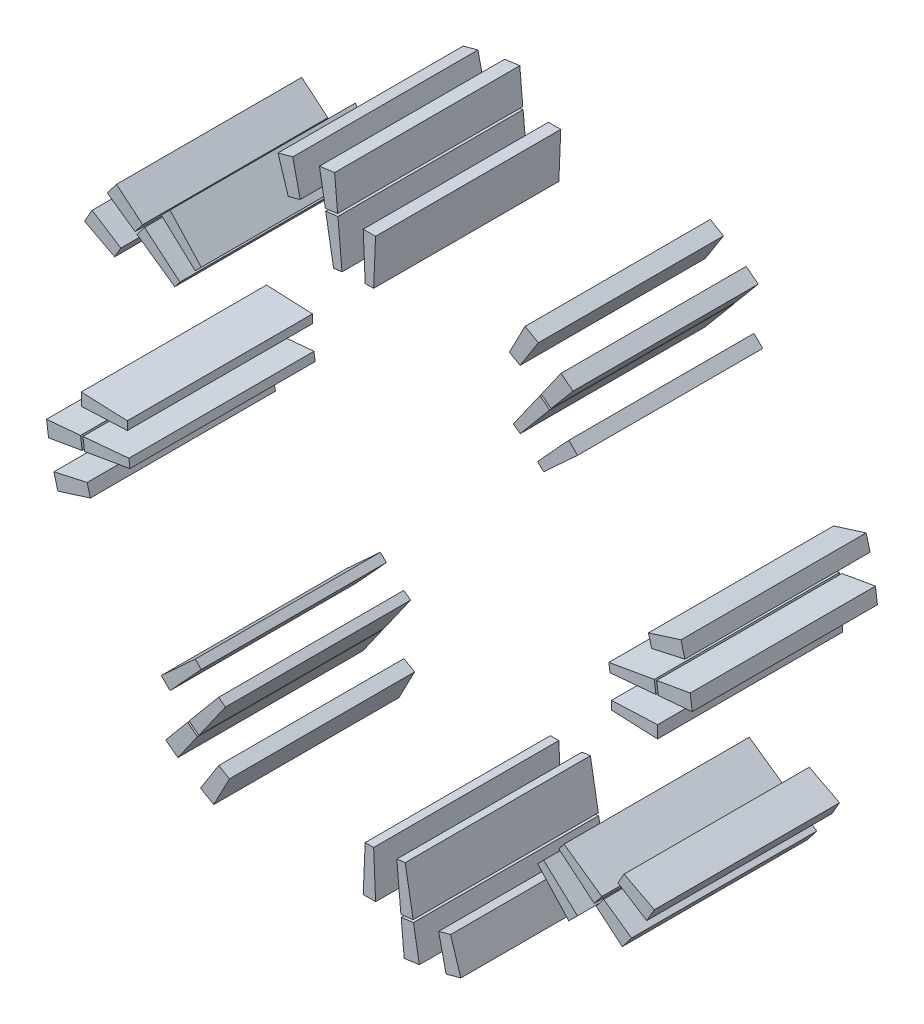
SolidWorks part; units mm, degrees
ref_plane "Спереди" through (0, 0, 0) normal (0, 0, 1) x (1, 0, 0)
ref_plane "Сверху" through (0, 0, 0) normal (0, 1, 0) x (1, 0, 0)
ref_plane "Справа" through (0, 0, 0) normal (1, 0, 0) x (0, 0, -1)
sketch "Эскиз1" plane through (0, 0, 0) normal (0, 0, 1) x (1, 0, 0)
  line L0 (39.2171, -0.6875) -> (46.6769, -1.0008)
  line L1 (46.6769, -1.0008) -> (46.6769, 1.0008)
  line L2 (46.6769, 1.0008) -> (39.2171, 0.6875)
  line L3 (39.2171, 0.6875) -> (39.2171, -0.6875)
  line L4 (46.7943, 5.1511) -> (52.2963, 5.6368)
  line L5 (52.2963, 5.6368) -> (51.9732, 8.0906)
  line L6 (51.9732, 8.0906) -> (46.533, 7.1357)
  line L7 (46.533, 7.1357) -> (46.7943, 5.1511)
  line L8 (38.9713, 4.4372) -> (46.4082, 5.1003)
  line L9 (46.4082, 5.1003) -> (46.147, 7.0848)
  line L10 (46.147, 7.0848) -> (38.7918, 5.8005)
  line L11 (38.7918, 5.8005) -> (38.9713, 4.4372)
  line L12 (45.7216, 11.2149) -> (51.1131, 12.4146)
  line L13 (51.1131, 12.4146) -> (50.4725, 14.8052)
  line L14 (50.4725, 14.8052) -> (45.2035, 13.1484)
  line L15 (45.2035, 13.1484) -> (45.7216, 11.2149)
  line L16 (28.2168, 27.2445) -> (33.7133, 32.2979)
  line L17 (33.7133, 32.2979) -> (32.2979, 33.7133)
  line L18 (32.2979, 33.7133) -> (27.2445, 28.2168)
  line L19 (27.2445, 28.2168) -> (28.2168, 27.2445)
  line L20 (29.4462, 36.7309) -> (32.9933, 40.9648)
  line L21 (32.9933, 40.9648) -> (31.0297, 42.4715)
  line L22 (31.0297, 42.4715) -> (27.8581, 37.9495)
  line L23 (27.8581, 37.9495) -> (29.4462, 36.7309)
  line L24 (24.4193, 30.6945) -> (29.2091, 36.422)
  line L25 (29.2091, 36.422) -> (27.6211, 37.6406)
  line L26 (27.6211, 37.6406) -> (23.3284, 31.5315)
  line L27 (23.3284, 31.5315) -> (24.4193, 30.6945)
  line L28 (24.3999, 40.2602) -> (27.364, 44.9209)
  line L29 (27.364, 44.9209) -> (25.2206, 46.1584)
  line L30 (25.2206, 46.1584) -> (22.6664, 41.261)
  line L31 (22.6664, 41.261) -> (24.3999, 40.2602)
  line L32 (0.6875, 39.2171) -> (1.0008, 46.6769)
  line L33 (1.0008, 46.6769) -> (-1.0008, 46.6769)
  line L34 (-1.0008, 46.6769) -> (-0.6875, 39.2171)
  line L35 (-0.6875, 39.2171) -> (0.6875, 39.2171)
  line L36 (-5.1511, 46.7943) -> (-5.6368, 52.2963)
  line L37 (-5.6368, 52.2963) -> (-8.0906, 51.9732)
  line L38 (-8.0906, 51.9732) -> (-7.1357, 46.533)
  line L39 (-7.1357, 46.533) -> (-5.1511, 46.7943)
  line L40 (-4.4372, 38.9713) -> (-5.1003, 46.4082)
  line L41 (-5.1003, 46.4082) -> (-7.0848, 46.147)
  line L42 (-7.0848, 46.147) -> (-5.8005, 38.7918)
  line L43 (-5.8005, 38.7918) -> (-4.4372, 38.9713)
  line L44 (-11.2149, 45.7216) -> (-12.4146, 51.1131)
  line L45 (-12.4146, 51.1131) -> (-14.8052, 50.4725)
  line L46 (-14.8052, 50.4725) -> (-13.1484, 45.2035)
  line L47 (-13.1484, 45.2035) -> (-11.2149, 45.7216)
  line L48 (-27.2445, 28.2168) -> (-32.2979, 33.7133)
  line L49 (-32.2979, 33.7133) -> (-33.7133, 32.2979)
  line L50 (-33.7133, 32.2979) -> (-28.2168, 27.2445)
  line L51 (-28.2168, 27.2445) -> (-27.2445, 28.2168)
  line L52 (-36.7309, 29.4462) -> (-40.9648, 32.9933)
  line L53 (-40.9648, 32.9933) -> (-42.4715, 31.0297)
  line L54 (-42.4715, 31.0297) -> (-37.9495, 27.8581)
  line L55 (-37.9495, 27.8581) -> (-36.7309, 29.4462)
  line L56 (-30.6945, 24.4193) -> (-36.422, 29.2091)
  line L57 (-36.422, 29.2091) -> (-37.6406, 27.6211)
  line L58 (-37.6406, 27.6211) -> (-31.5315, 23.3284)
  line L59 (-31.5315, 23.3284) -> (-30.6945, 24.4193)
  line L60 (-40.2602, 24.3999) -> (-44.9209, 27.364)
  line L61 (-44.9209, 27.364) -> (-46.1584, 25.2206)
  line L62 (-46.1584, 25.2206) -> (-41.261, 22.6664)
  line L63 (-41.261, 22.6664) -> (-40.2602, 24.3999)
  line L64 (-39.2171, 0.6875) -> (-46.6769, 1.0008)
  line L65 (-46.6769, 1.0008) -> (-46.6769, -1.0008)
  line L66 (-46.6769, -1.0008) -> (-39.2171, -0.6875)
  line L67 (-39.2171, -0.6875) -> (-39.2171, 0.6875)
  line L68 (-46.7943, -5.1511) -> (-52.2963, -5.6368)
  line L69 (-52.2963, -5.6368) -> (-51.9732, -8.0906)
  line L70 (-51.9732, -8.0906) -> (-46.533, -7.1357)
  line L71 (-46.533, -7.1357) -> (-46.7943, -5.1511)
  line L72 (-38.9713, -4.4372) -> (-46.4082, -5.1003)
  line L73 (-46.4082, -5.1003) -> (-46.147, -7.0848)
  line L74 (-46.147, -7.0848) -> (-38.7918, -5.8005)
  line L75 (-38.7918, -5.8005) -> (-38.9713, -4.4372)
  line L76 (-45.7216, -11.2149) -> (-51.1131, -12.4146)
  line L77 (-51.1131, -12.4146) -> (-50.4725, -14.8052)
  line L78 (-50.4725, -14.8052) -> (-45.2035, -13.1484)
  line L79 (-45.2035, -13.1484) -> (-45.7216, -11.2149)
  line L80 (-28.2168, -27.2445) -> (-33.7133, -32.2979)
  line L81 (-33.7133, -32.2979) -> (-32.2979, -33.7133)
  line L82 (-32.2979, -33.7133) -> (-27.2445, -28.2168)
  line L83 (-27.2445, -28.2168) -> (-28.2168, -27.2445)
  line L84 (-29.4462, -36.7309) -> (-32.9933, -40.9648)
  line L85 (-32.9933, -40.9648) -> (-31.0297, -42.4715)
  line L86 (-31.0297, -42.4715) -> (-27.8581, -37.9495)
  line L87 (-27.8581, -37.9495) -> (-29.4462, -36.7309)
  line L88 (-24.4193, -30.6945) -> (-29.2091, -36.422)
  line L89 (-29.2091, -36.422) -> (-27.6211, -37.6406)
  line L90 (-27.6211, -37.6406) -> (-23.3284, -31.5315)
  line L91 (-23.3284, -31.5315) -> (-24.4193, -30.6945)
  line L92 (-24.3999, -40.2602) -> (-27.364, -44.9209)
  line L93 (-27.364, -44.9209) -> (-25.2206, -46.1584)
  line L94 (-25.2206, -46.1584) -> (-22.6664, -41.261)
  line L95 (-22.6664, -41.261) -> (-24.3999, -40.2602)
  line L96 (-0.6875, -39.2171) -> (-1.0008, -46.6769)
  line L97 (-1.0008, -46.6769) -> (1.0008, -46.6769)
  line L98 (1.0008, -46.6769) -> (0.6875, -39.2171)
  line L99 (0.6875, -39.2171) -> (-0.6875, -39.2171)
  line L100 (5.1511, -46.7943) -> (5.6368, -52.2963)
  line L101 (5.6368, -52.2963) -> (8.0906, -51.9732)
  line L102 (8.0906, -51.9732) -> (7.1357, -46.533)
  line L103 (7.1357, -46.533) -> (5.1511, -46.7943)
  line L104 (4.4372, -38.9713) -> (5.1003, -46.4082)
  line L105 (5.1003, -46.4082) -> (7.0848, -46.147)
  line L106 (7.0848, -46.147) -> (5.8005, -38.7918)
  line L107 (5.8005, -38.7918) -> (4.4372, -38.9713)
  line L108 (11.2149, -45.7216) -> (12.4146, -51.1131)
  line L109 (12.4146, -51.1131) -> (14.8052, -50.4725)
  line L110 (14.8052, -50.4725) -> (13.1484, -45.2035)
  line L111 (13.1484, -45.2035) -> (11.2149, -45.7216)
  line L112 (27.2445, -28.2168) -> (32.2979, -33.7133)
  line L113 (32.2979, -33.7133) -> (33.7133, -32.2979)
  line L114 (33.7133, -32.2979) -> (28.2168, -27.2445)
  line L115 (28.2168, -27.2445) -> (27.2445, -28.2168)
  line L116 (36.7309, -29.4462) -> (40.9648, -32.9933)
  line L117 (40.9648, -32.9933) -> (42.4715, -31.0297)
  line L118 (42.4715, -31.0297) -> (37.9495, -27.8581)
  line L119 (37.9495, -27.8581) -> (36.7309, -29.4462)
  line L120 (30.6945, -24.4193) -> (36.422, -29.2091)
  line L121 (36.422, -29.2091) -> (37.6406, -27.6211)
  line L122 (37.6406, -27.6211) -> (31.5315, -23.3284)
  line L123 (31.5315, -23.3284) -> (30.6945, -24.4193)
  line L124 (40.2602, -24.3999) -> (44.9209, -27.364)
  line L125 (44.9209, -27.364) -> (46.1584, -25.2206)
  line L126 (46.1584, -25.2206) -> (41.261, -22.6664)
  line L127 (41.261, -22.6664) -> (40.2602, -24.3999)
extrude "Slot_copper_envelopes" add sketch "Эскиз1" along normal blind 30 from offset 15 separate body
